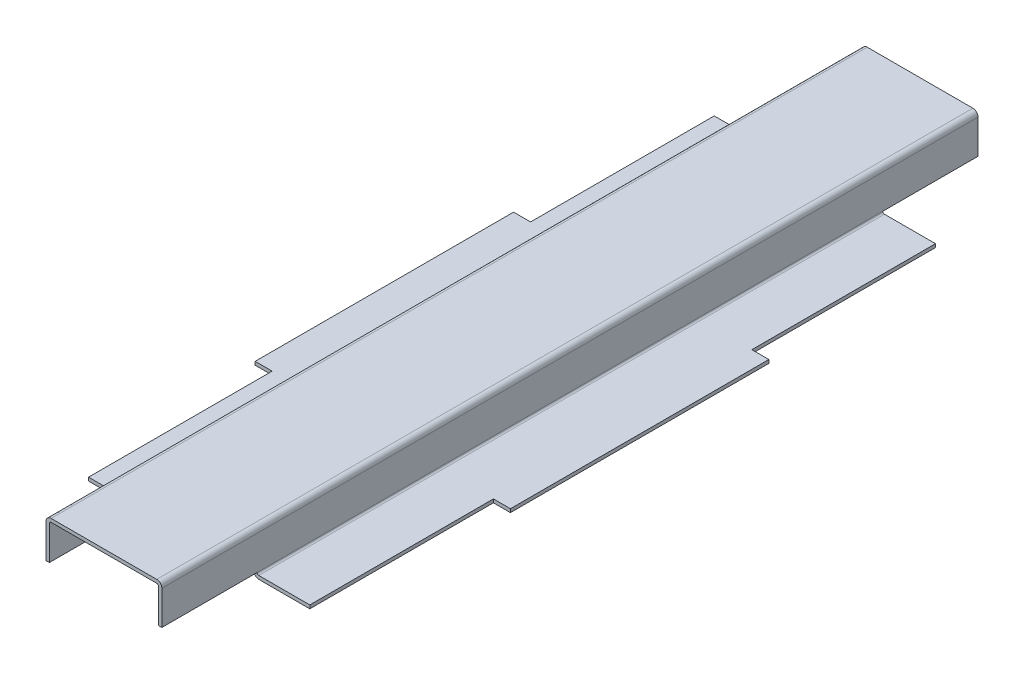
SolidWorks part; units mm, degrees
ref_plane "Front Plane" through (0, 0, 0) normal (0, 0, 1) x (1, 0, 0)
ref_plane "Top Plane" through (0, 0, 0) normal (0, 1, 0) x (1, 0, 0)
ref_plane "Right Plane" through (0, 0, 0) normal (1, 0, 0) x (0, 0, -1)
sketch "Sketch1" plane through (0, 0, 0) normal (0, 0, 1) x (1, 0, 0)
  line L0 (-98.65, 0) -> (98.65, 0)
  line L1 (-105, -6.35) -> (-105, -69.85)
  line L2 (-111.35, -76.2) -> (-206.6, -76.2)
  line L3 (0, 0) -> (0, 103.2924) construction
  line L4 (111.35, -76.2) -> (206.6, -76.2)
  line L5 (105, -6.35) -> (105, -69.85)
  arc A0 (-111.35, -76.2) -> (-105, -69.85) centre (-111.35, -69.85) ccw
  arc A1 (-105, -6.35) -> (-98.65, 0) centre (-98.65, -6.35) cw
  arc A2 (111.35, -76.2) -> (105, -69.85) centre (111.35, -69.85) cw
  arc A3 (105, -6.35) -> (98.65, 0) centre (98.65, -6.35) ccw
  point P3 (0, 0)
  point P11 (0, 0)
  point P12 (-105, -76.2)
  point P15 (-105, 0)
  point P23 (0, 0)
  dimension "D4" = 6.35
  dimension "D1" = 105
  dimension "D2" = 76.2
  dimension "D3" = 101.6
extrude "Extrude-Thin1" add sketch "Sketch1" along normal mid plane 1168.4 thin thin type mid plane wall 6.35
sketch "Sketch3" plane through (0, 0, 584.2) normal (0, 0, 1) x (1, 0, 0)
  line L12 (-108.175, -69.85) -> (-101.825, -69.85)
  line L13 (101.825, -69.85) -> (108.175, -69.85)
  line L24 (111.35, -79.375) -> (206.6, -79.375)
  line L25 (206.6, -79.375) -> (206.6, -73.025)
  line L26 (206.6, -73.025) -> (111.35, -73.025)
  line L27 (108.175, -69.85) -> (108.175, -6.35)
  line L28 (98.65, 3.175) -> (-98.65, 3.175)
  line L29 (-108.175, -6.35) -> (-108.175, -69.85)
  line L30 (-111.35, -73.025) -> (-206.6, -73.025)
  line L31 (-206.6, -73.025) -> (-206.6, -79.375)
  line L32 (-206.6, -79.375) -> (-111.35, -79.375)
  line L33 (-101.825, -69.85) -> (-101.825, -6.35)
  line L34 (-98.65, -3.175) -> (98.65, -3.175)
  line L35 (101.825, -6.35) -> (101.825, -69.85)
  line L39 (108.175, -69.85) -> (108.175, -6.35)
  line L40 (98.65, 3.175) -> (-98.65, 3.175)
  line L41 (-108.175, -6.35) -> (-108.175, -69.85)
  line L45 (-101.825, -69.85) -> (-101.825, -6.35)
  line L46 (-98.65, -3.175) -> (98.65, -3.175)
  line L47 (101.825, -6.35) -> (101.825, -69.85)
  arc A16 (108.175, -69.85) -> (111.35, -73.025) centre (111.35, -69.85) ccw
  arc A17 (108.175, -6.35) -> (98.65, 3.175) centre (98.65, -6.35) ccw
  arc A18 (-98.65, 3.175) -> (-108.175, -6.35) centre (-98.65, -6.35) ccw
  arc A19 (-111.35, -73.025) -> (-108.175, -69.85) centre (-111.35, -69.85) ccw
  arc A20 (-111.35, -79.375) -> (-101.825, -69.85) centre (-111.35, -69.85) ccw
  arc A21 (-98.65, -3.175) -> (-101.825, -6.35) centre (-98.65, -6.35) ccw
  arc A22 (101.825, -6.35) -> (98.65, -3.175) centre (98.65, -6.35) ccw
  arc A23 (101.825, -69.85) -> (111.35, -79.375) centre (111.35, -69.85) ccw
  arc A25 (108.175, -6.35) -> (98.65, 3.175) centre (98.65, -6.35) ccw
  arc A26 (-98.65, 3.175) -> (-108.175, -6.35) centre (-98.65, -6.35) ccw
  arc A29 (-98.65, -3.175) -> (-101.825, -6.35) centre (-98.65, -6.35) ccw
  arc A30 (101.825, -6.35) -> (98.65, -3.175) centre (98.65, -6.35) ccw
  dimension "D1" = 0
extrude "Boss-Extrude1" add sketch "Sketch3" along normal blind 177.8
sketch "Sketch4" plane through (206.6, 0, 0) normal (1, 0, 0) x (0, 0, -1)
  line L2 (-584.2, -79.375) -> (584.2, -79.375) construction
  line L3 (-584.2, -73.025) -> (584.2, -73.025) construction
  line L4 (-241.3, -79.375) -> (241.3, -79.375)
  line L5 (-241.3, -79.375) -> (-241.3, -73.025)
  line L6 (-241.3, -73.025) -> (241.3, -73.025)
  line L7 (241.3, -79.375) -> (241.3, -73.025)
  point P1 (0, -79.375)
  point P2 (0, -79.375)
  dimension "D1" = 482.6
extrude "Boss-Extrude2" add sketch "Sketch4" along normal blind 31.75
mirror "Mirror1" about plane through (0, 0, 0) normal (0, 0, 1) of "Boss-Extrude1"
mirror "Mirror2" about plane through (0, 0, 0) normal (1, 0, 0) of "Boss-Extrude2"
